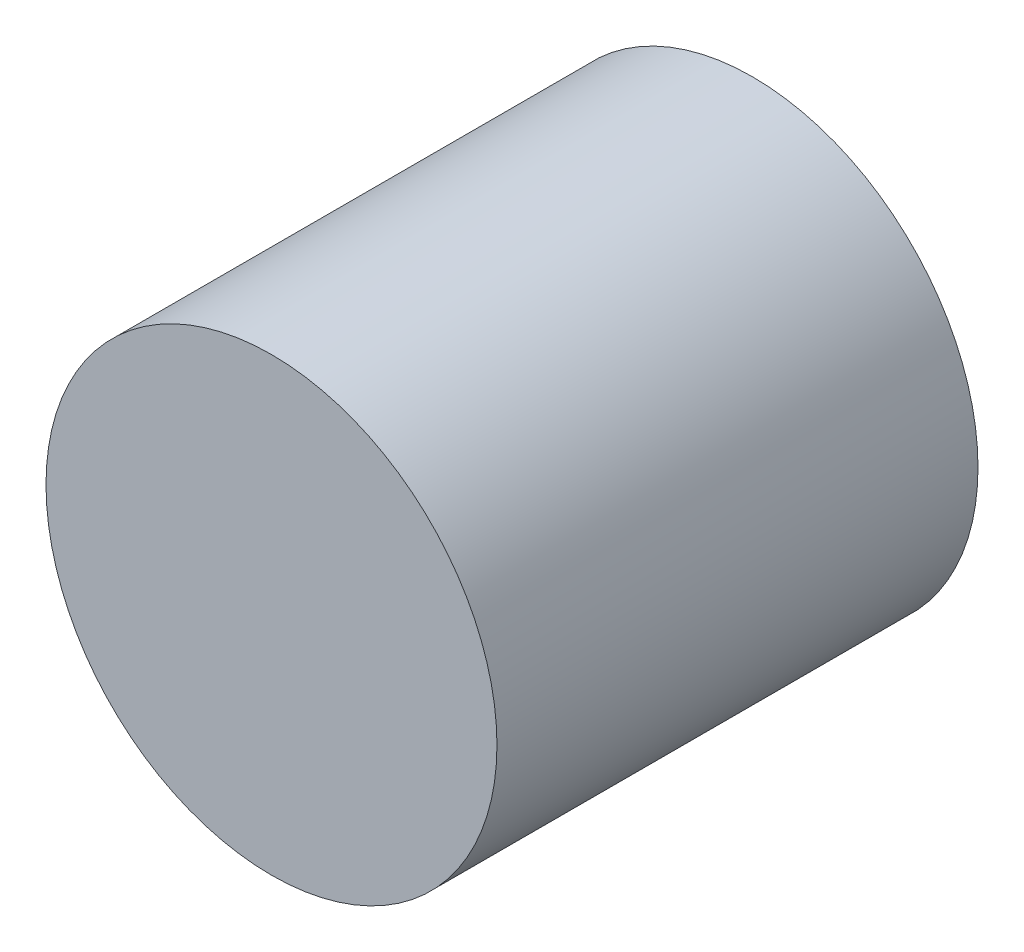
SolidWorks part; units mm, degrees
ref_plane "前视基准面" through (0, 0, 0) normal (0, 0, 1) x (1, 0, 0)
ref_plane "上视基准面" through (0, 0, 0) normal (0, 1, 0) x (1, 0, 0)
ref_plane "右视基准面" through (0, 0, 0) normal (1, 0, 0) x (0, 0, -1)
sketch "草图1" plane through (0, 0, 0) normal (0, 0, 1) x (1, 0, 0)
  circle A0 centre (-25.6563, 30) radius 7.5
  dimension "D1" = 15
extrude "凸台-拉伸1" add sketch "草图1" along normal blind 16
